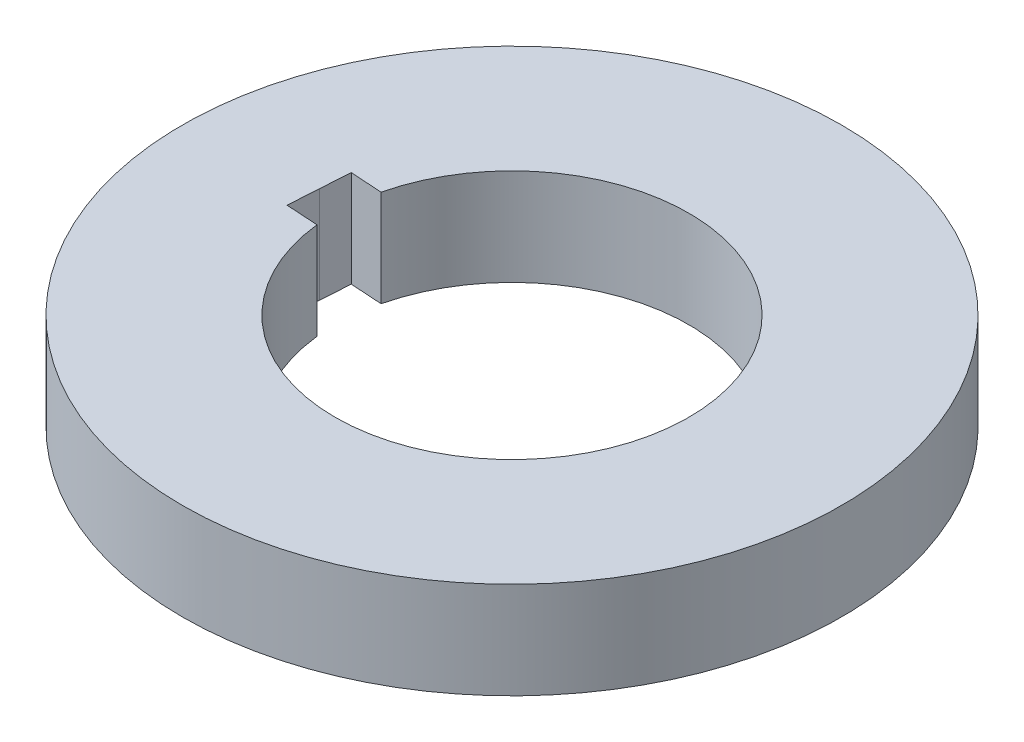
SolidWorks part; units mm, degrees
ref_plane "前基準面" through (0, 0, 0) normal (0, 0, 1) x (1, 0, 0)
ref_plane "上基準面" through (0, 0, 0) normal (0, 1, 0) x (1, 0, 0)
ref_plane "右基準面" through (0, 0, 0) normal (1, 0, 0) x (0, 0, -1)
sketch "草圖1" plane through (0, 0, 0) normal (0, 1, 0) x (1, 0, 0)
  circle A0 centre (0, 0) radius 17.05
extrude "填料-伸長1" add sketch "草圖1" along normal blind 5
sketch "草圖2" plane through (0, 5, 0) normal (0, 1, 0) x (1, 0, 0)
  circle A0 centre (0, 0) radius 9.15
extrude "除料-伸長1" cut sketch "草圖2" against normal blind 5
sketch "草圖3" plane through (0, 5, 0) normal (0, 1, 0) x (1, 0, 0)
  line L2 (-10.648, 0.6852) -> (-10.5484, 2.232)
  line L3 (-10.648, 0.6852) -> (-10.7471, -0.8899)
  line L4 (-10.5484, 2.232) -> (-8.8996, 2.1259)
  line L5 (-10.7471, -0.8899) -> (-9.0959, -0.9938)
  line L6 (-9.0959, -0.9938) -> (-8.8996, 2.1259)
  circle A2 centre (0, 0) radius 9.15 construction
extrude "除料-伸長2" cut sketch "草圖3" against normal through all
sketch "草圖4" plane through (0, 5, 0) normal (0, 1, 0) x (1, 0, 0)
  line L0 (-10.648, 0.6852) -> (0, 0)
